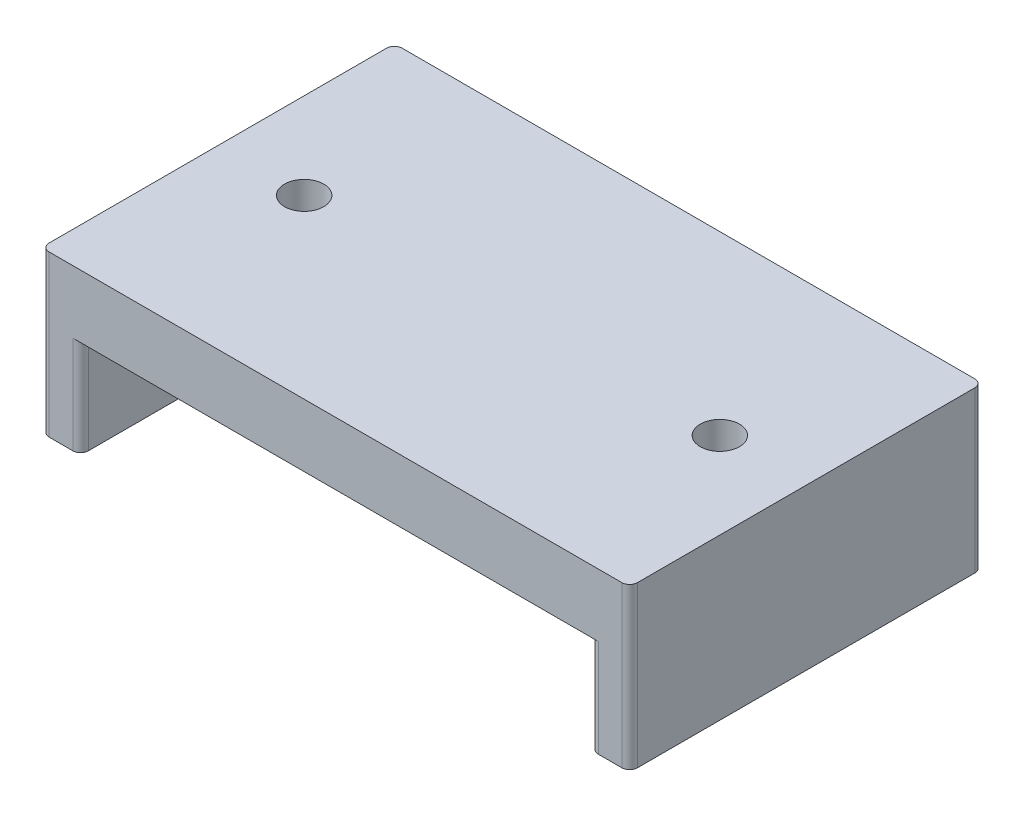
SolidWorks part; units mm, degrees
ref_plane "Front Plane" through (0, 0, 0) normal (0, 0, 1) x (1, 0, 0)
ref_plane "Top Plane" through (0, 0, 0) normal (0, 1, 0) x (1, 0, 0)
ref_plane "Right Plane" through (0, 0, 0) normal (1, 0, 0) x (0, 0, -1)
sketch "Sketch1" plane through (0, 0, 0) normal (0, 0, 1) x (1, 0, 0)
  line L0 (0, 0) -> (5, 0)
  line L1 (5, 0) -> (5, 12.45)
  line L2 (5, 12.45) -> (70, 12.45)
  line L3 (70, 12.45) -> (70, 0)
  line L4 (70, 0) -> (75, 0)
  line L5 (75, 0) -> (75, 20.45)
  line L6 (75, 20.45) -> (0, 20.45)
  line L7 (0, 20.45) -> (0, 0)
  line L8 (0, 0) -> (37.5, 0) construction
  line L9 (37.5, 0) -> (75, 0) construction
  dimension "D1" = 5
  dimension "D2" = 12.45
  dimension "D3" = 8
  dimension "D4" = 75
extrude "Boss-Extrude1" add sketch "Sketch1" along normal blind 45
sketch "Sketch2" plane through (0, 12.45, 0) normal (0, -1, 0) x (1, 0, 0)
  line L0 (11, 22.5) -> (64, 22.5) construction
  line L1 (37.5, 45) -> (37.5, 0) construction
  line L2 (5, 45) -> (70, 45) construction
  line L3 (5, 0) -> (70, 0) construction
  circle A0 centre (11, 22.5) radius 2.5
  circle A1 centre (64, 22.5) radius 2.5
  point P4 (37.5, 22.5)
  point P11 (37.5, 22.5)
  dimension "D1" = 5
  dimension "D2" = 53
extrude "Cut-Extrude1" cut sketch "Sketch2" against normal through all
fillet "Fillet1" radius 1 8 edges at (70, 6.225, 45) (75, 10.225, 45) (70, 6.225, 0) (75, 10.225, 0) (5, 6.225, 0) (0, 10.225, 0) (0, 10.225, 45) (5, 6.225, 45)
